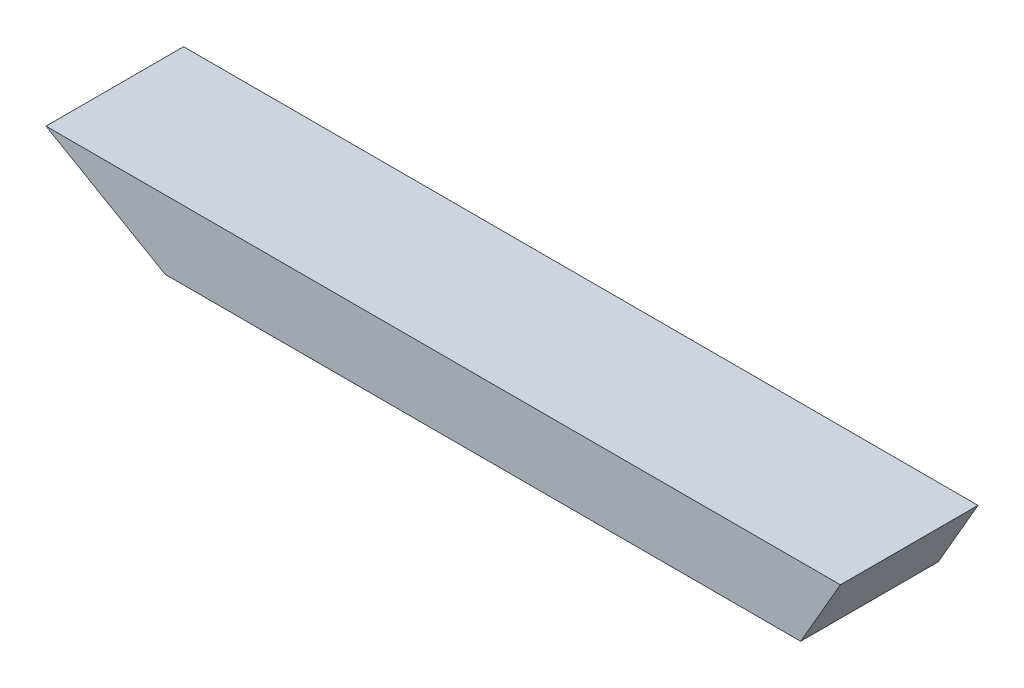
SolidWorks part; units mm, degrees
material "Pine"
ref_plane "Alzado" through (0, 0, 0) normal (0, 0, 1) x (1, 0, 0)
ref_plane "Planta" through (0, 0, 0) normal (0, 1, 0) x (1, 0, 0)
ref_plane "Vista lateral" through (0, 0, 0) normal (1, 0, 0) x (0, 0, -1)
sketch "Sketch1" plane through (0, 0, 0) normal (0, 1, 0) x (1, 0, 0)
  line L1 (-146.65, -25.4) -> (146.65, -25.4)
  line L2 (-146.65, -25.4) -> (-146.65, 25.4)
  line L3 (-146.65, 25.4) -> (146.65, 25.4)
  line L4 (146.65, -25.4) -> (146.65, 25.4)
  line L5 (-146.65, -25.4) -> (146.65, 25.4) construction
  line L6 (-146.65, 25.4) -> (146.65, -25.4) construction
  point P0 (0, 0)
  dimension "D1" = 50.8
  dimension "D2" = 293.3
extrude "Boss-Extrude1" add sketch "Sketch1" along normal blind 25.4
sketch "Sketch2" plane through (0, 0, 25.4) normal (0, 0, 1) x (1, 0, 0)
  line L0 (-146.65, 25.4) -> (-102.6559, 0)
  line L1 (-146.65, 0) -> (146.65, 0) construction
  line L2 (-102.6559, 0) -> (-146.65, 0)
  line L3 (-146.65, 0) -> (-146.65, 25.4)
  line L4 (146.65, 25.4) -> (131.9853, 0)
  line L5 (146.65, 25.4) -> (146.65, 0) construction
  line L6 (131.9853, 0) -> (146.65, 0)
  line L7 (146.65, 0) -> (146.65, 25.4)
  dimension "D1" = 60
  dimension "D2" = 30
extrude "Cut-Extrude1" cut sketch "Sketch2" against normal up to surface (50.8 mm away) up to face at (0, 12.7, -25.4)
equation "\"1i\"=10"
